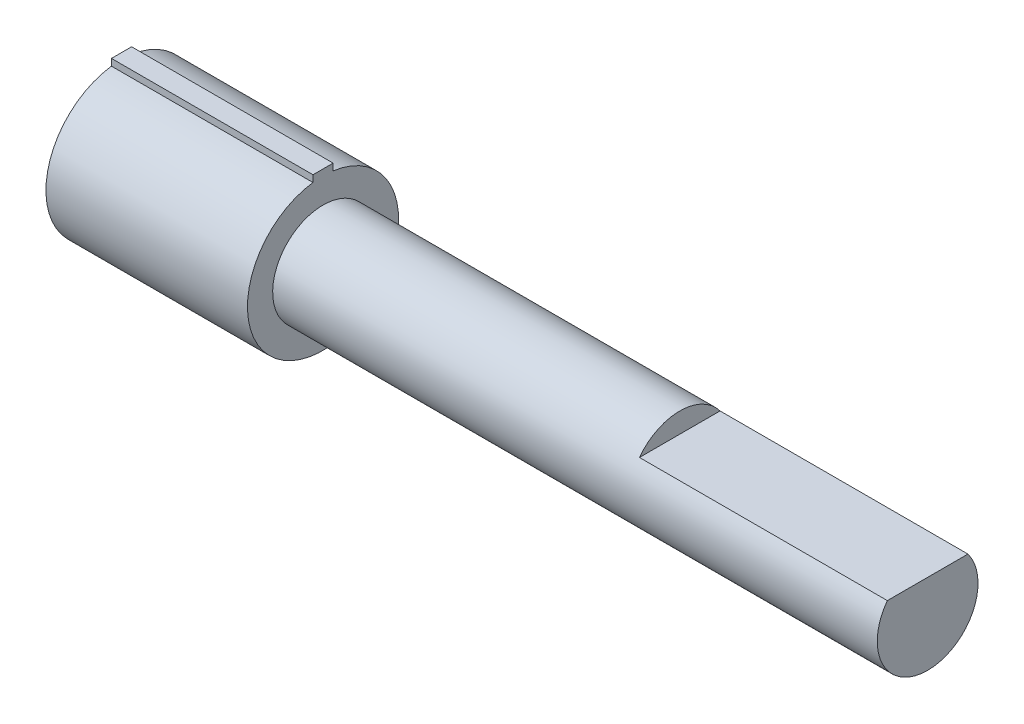
SolidWorks part; units mm, degrees
ref_plane "Front Plane" through (0, 0, 0) normal (0, 0, 1) x (1, 0, 0)
ref_plane "Top Plane" through (0, 0, 0) normal (0, 1, 0) x (1, 0, 0)
ref_plane "Right Plane" through (0, 0, 0) normal (1, 0, 0) x (0, 0, -1)
sketch "Sketch1" plane through (0, 0, 0) normal (1, 0, 0) x (0, 0, -1)
  circle A0 centre (0, 0) radius 4.7625
  circle A1 centre (0, 0) radius 1.5875
  circle A2 centre (0, 0) radius 2.54
  dimension "D1" = 9.525
  dimension "D2" = 3.175
  dimension "D3" = 5.08
extrude "Boss-Extrude1" add sketch "Sketch1" along normal blind 12.7 contours A0 A2 | A2 A1 | A1
sketch "Sketch2" plane through (0, 0, 0) normal (-1, 0, 0) x (0, 0, 1)
  circle A0 centre (0, 0) radius 2.54
  dimension "D1" = 5.08
extrude "Cut-Extrude1" cut sketch "Sketch2" against normal blind 9.525
sketch "Sketch3" plane through (12.7, 0, 0) normal (1, 0, 0) x (0, 0, -1)
  circle A0 centre (0, 0) radius 3.175
  dimension "D1" = 6.35
extrude "Boss-Extrude2" add sketch "Sketch3" along normal blind 38.1
sketch "Sketch4" plane through (12.7, 0, 0) normal (1, 0, 0) x (0, 0, -1)
  line L0 (0, 0) -> (0, 4.7625) construction
  line L2 (-0.635, 4.3815) -> (0.635, 4.3815)
  line L3 (-0.635, 4.3815) -> (-0.635, 5.1435)
  line L4 (-0.635, 5.1435) -> (0.635, 5.1435)
  line L5 (0.635, 4.3815) -> (0.635, 5.1435)
  line L6 (-0.635, 4.3815) -> (0.635, 5.1435) construction
  line L7 (-0.635, 5.1435) -> (0.635, 4.3815) construction
  circle A0 centre (0, 0) radius 4.7625 construction
  dimension "D1" = 1.27
  dimension "D2" = 0.762
extrude "Boss-Extrude3" add sketch "Sketch4" against normal up to surface (12.7 mm away) up to face at (0, 0, 2.54)
sketch "Sketch5" plane through (50.8, 0, 0) normal (1, 0, 0) x (0, 0, -1)
  line L0 (-2.54, 1.905) -> (2.54, 1.905)
  circle A0 centre (0, 0) radius 3.175 construction
  arc A1 (-2.54, 1.905) -> (2.54, 1.905) centre (0, 0) cw
  dimension "D1" = 1.905
extrude "Cut-Extrude2" cut sketch "Sketch5" against normal blind 15.621
